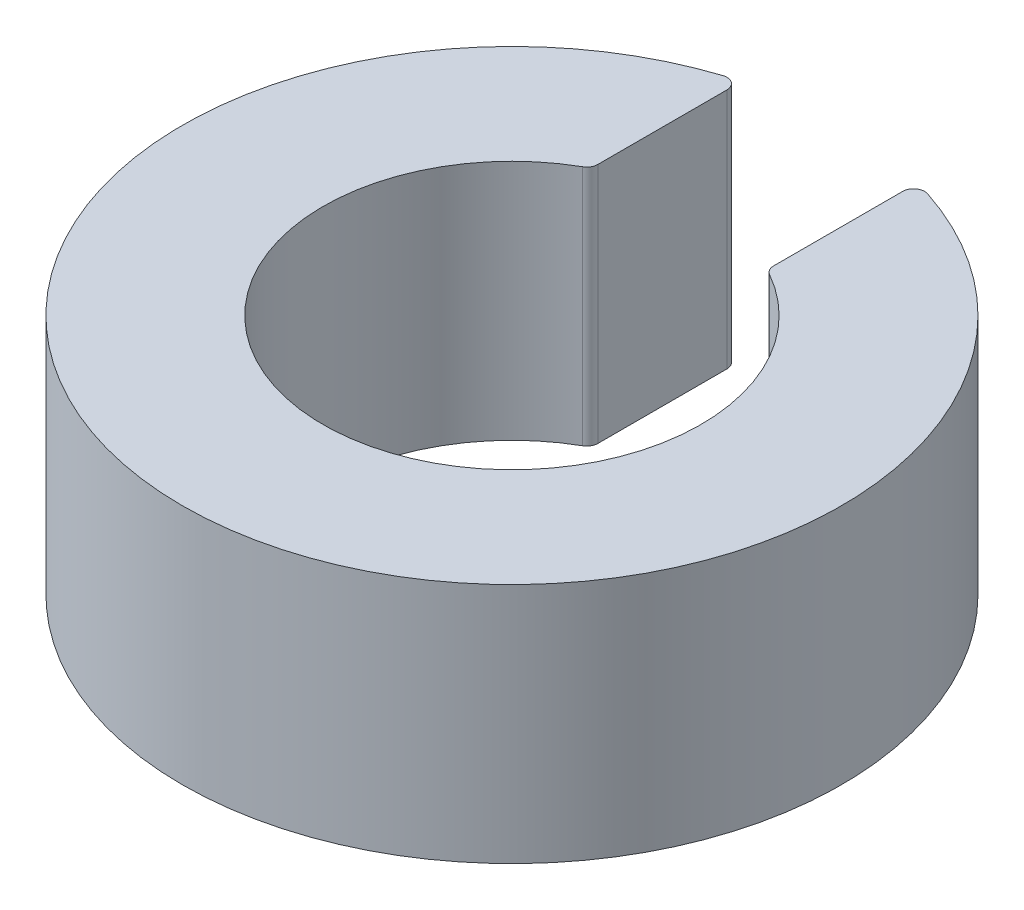
SolidWorks part; units mm, degrees
material "ABS"
ref_plane "Front Plane" through (0, 0, 0) normal (0, 0, 1) x (1, 0, 0)
ref_plane "Top Plane" through (0, 0, 0) normal (0, 1, 0) x (1, 0, 0)
ref_plane "Right Plane" through (0, 0, 0) normal (1, 0, 0) x (0, 0, -1)
sketch "Sketch1" plane through (0, 0, 0) normal (0, 1, 0) x (1, 0, 0)
  line L0 (-2, 7.2284) -> (-2, 3.8066)
  line L1 (2, 7.2284) -> (2, 3.8066)
  line L2 (-2, 3.8066) -> (2, 3.8066) construction
  circle A0 centre (0, 0) radius 7.5
  circle A1 centre (0, 0) radius 4.3
  point P8 (0, 3.8066)
  dimension "D2" = 15
  dimension "D3" = 8.6
  dimension "D1" = 4
extrude "Boss-Extrude1" add sketch "Sketch1" along normal blind 5.5 contours A1 L0 A0 L1
fillet "Fillet1" radius 0.25 4 edges at (2, 2.75, -7.2284) (-2, 2.75, -7.2284) (2, 2.75, -3.8066) (-2, 2.75, -3.8066)
